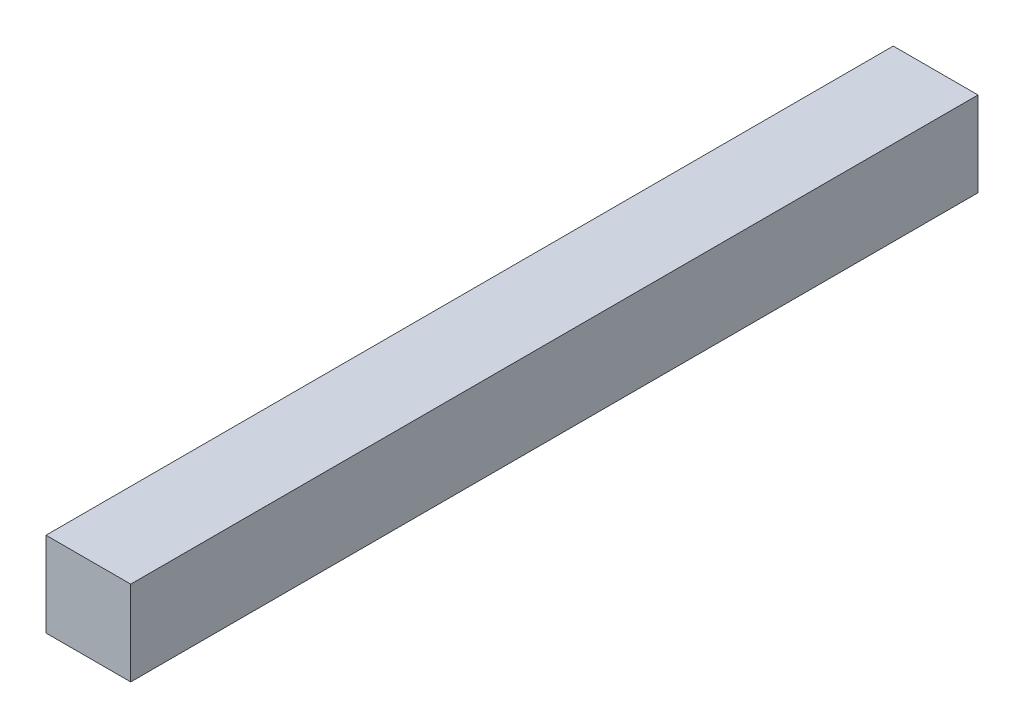
SolidWorks part; units mm, degrees
ref_plane "Front Plane" through (0, 0, 0) normal (0, 0, 1) x (1, 0, 0)
ref_plane "Top Plane" through (0, 0, 0) normal (0, 1, 0) x (1, 0, 0)
ref_plane "Right Plane" through (0, 0, 0) normal (1, 0, 0) x (0, 0, -1)
sketch "Sketch1" plane through (0, 0, 0) normal (0, 0, 1) x (1, 0, 0)
  line L1 (0, 0) -> (10, 0)
  line L2 (0, 0) -> (0, 10)
  line L3 (0, 10) -> (10, 10)
  line L4 (10, 0) -> (10, 10)
  dimension "D1" = 10
extrude "Boss-Extrude1" add sketch "Sketch1" along normal blind 100
